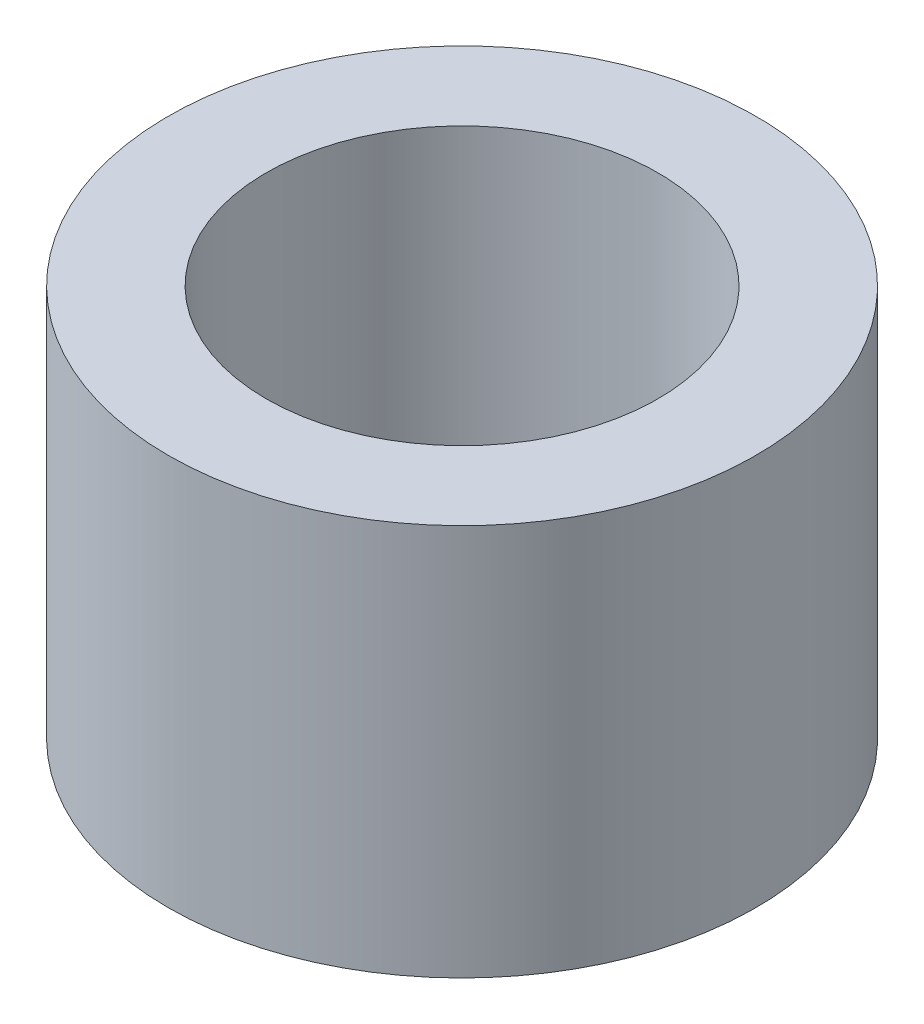
SolidWorks part; units mm, degrees
ref_plane "Front Plane" through (0, 0, 0) normal (0, 0, 1) x (1, 0, 0)
ref_plane "Top Plane" through (0, 0, 0) normal (0, 1, 0) x (1, 0, 0)
ref_plane "Right Plane" through (0, 0, 0) normal (1, 0, 0) x (0, 0, -1)
sketch "Sketch1" plane through (0, 0, 0) normal (0, 1, 0) x (1, 0, 0)
  circle A0 centre (0, 0) radius 3
  circle A1 centre (0, 0) radius 4.5
  dimension "D1" = 9
  dimension "D2" = 6
extrude "Boss-Extrude1" add sketch "Sketch1" along normal blind 6
